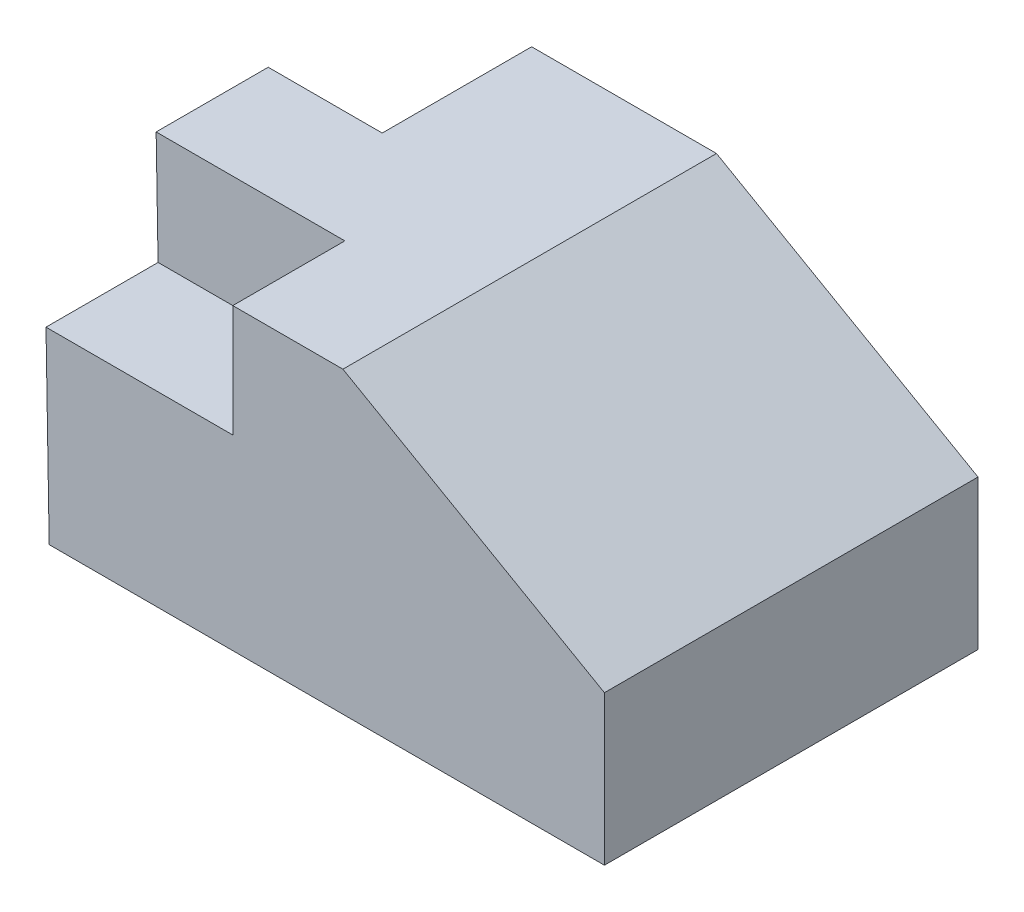
SolidWorks part; units mm, degrees
ref_plane "Front Plane" through (0, 0, 0) normal (0, 0, 1) x (1, 0, 0)
ref_plane "Top Plane" through (0, 0, 0) normal (0, 1, 0) x (1, 0, 0)
ref_plane "Right Plane" through (0, 0, 0) normal (1, 0, 0) x (0, 0, -1)
sketch "Sketch1" plane through (0, 0, 0) normal (0, 0, 1) x (1, 0, 0)
  line L7 (1.3718, 0) -> (150, 0)
  line L12 (150, 0) -> (150, 40)
  line L13 (150, 40) -> (80, 80)
  line L14 (80, 80) -> (0, 80)
  line L15 (0, 80) -> (1.3718, 0)
  dimension "D2" = 40
  dimension "D3" = 80
  dimension "D4" = 80
extrude "Boss-Extrude1" add sketch "Sketch1" against normal blind 100 contours L14 L15 L7 L12 L13
sketch "Sketch2" plane through (0, 0, 0) normal (0, 0, 1) x (1, 0, 0)
  line L0 (0, 80) -> (0.5144, 50)
  line L1 (0, 80) -> (1.3718, 0) construction
  line L2 (0.5144, 50) -> (50.5144, 50)
  line L3 (50.5144, 50) -> (50.5144, 80)
  line L4 (80, 80) -> (0, 80) construction
  line L5 (50.5144, 80) -> (0, 80)
  dimension "D1" = 50
  dimension "D2" = 30
extrude "Cut-Extrude1" cut sketch "Sketch2" against normal blind 30
sketch "Sketch3" plane through (0, 0, -100) normal (0, 0, -1) x (-1, 0, 0)
  line L0 (0, 80) -> (-30.5144, 80)
  line L1 (-80, 80) -> (0, 80) construction
  line L2 (-30.5144, 80) -> (-30.5144, 50)
  line L3 (-30.5144, 50) -> (-0.5144, 50)
  line L4 (0, 80) -> (-1.3718, 0) construction
  line L5 (-0.5144, 50) -> (0, 80)
  dimension "D1" = 30
  dimension "D2" = 30
extrude "Cut-Extrude2" cut sketch "Sketch3" against normal blind 40 contours L0 L2 L3 L5
sketch "Sketch5" plane through (0, 50, 0) normal (0, 1, 0) x (1, 0, 0)
  line L0 (0, 60) -> (30.5144, 60) construction
  line L1 (0.5144, 100) -> (30.5144, 100)
  line L2 (0.5144, 100) -> (0.5144, 60)
  line L3 (0.5144, 60) -> (30.5144, 60)
  line L4 (30.5144, 100) -> (30.5144, 60)
  line L5 (30.5144, 60) -> (0.5144, 60) construction
extrude "Cut-Extrude3" cut sketch "Sketch5" against normal through all contours L2 L3 L4 L1
